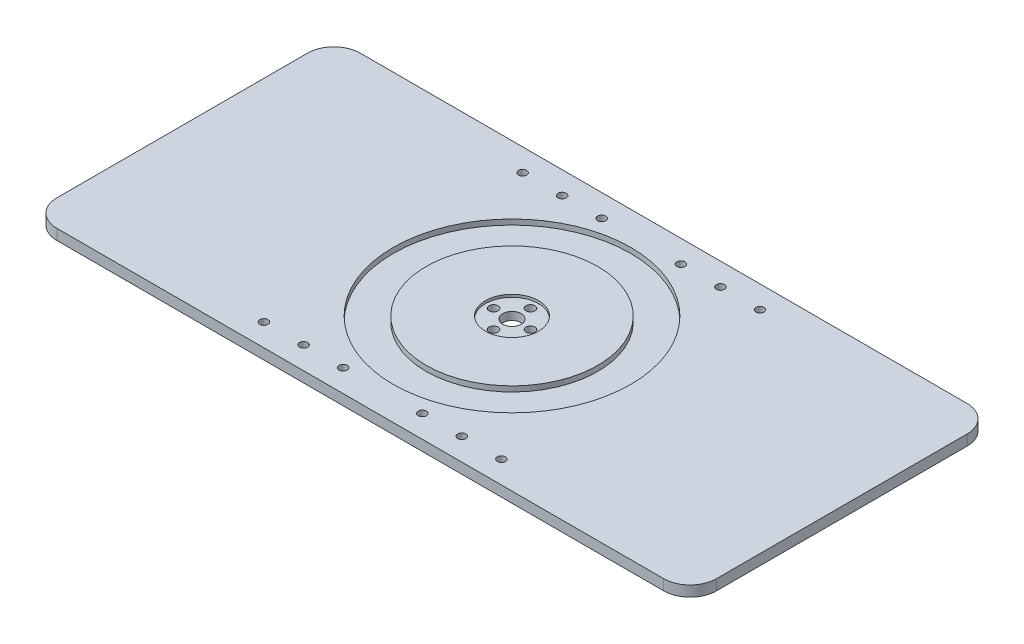
SolidWorks part; units mm, degrees
ref_plane "前视基准面" through (0, 0, 0) normal (0, 0, 1) x (1, 0, 0)
ref_plane "上视基准面" through (0, 0, 0) normal (0, 1, 0) x (1, 0, 0)
ref_plane "右视基准面" through (0, 0, 0) normal (1, 0, 0) x (0, 0, -1)
other "Configuration Table"
sketch "草图1" plane through (0, 0, 0) normal (0, 1, 0) x (1, 0, 0)
  line L0 (-93.4397, 0) -> (118.7468, 0) construction
  line L1 (-125, -57.5) -> (125, -57.5)
  line L2 (-125, -57.5) -> (-125, 57.5)
  line L3 (-125, 57.5) -> (125, 57.5)
  line L4 (125, -57.5) -> (125, 57.5)
  line L5 (-125, -57.5) -> (125, 57.5) construction
  line L6 (-125, 57.5) -> (125, -57.5) construction
  line L7 (0, 92.3971) -> (0, -129.74) construction
  circle A0 centre (0, 0) radius 45.1 construction
  circle A1 centre (0, 0) radius 3.5
  circle A2 centre (45, 49) radius 1.55
  circle A3 centre (45, -49) radius 1.55
  circle A4 centre (-45, -49) radius 1.55
  circle A5 centre (-45, 49) radius 1.55
  circle A6 centre (-15, -49) radius 1.55
  circle A7 centre (15, -49) radius 1.55
  circle A8 centre (15, 49) radius 1.55
  circle A9 centre (-15, 49) radius 1.55
  circle A10 centre (30, 49) radius 1.55
  circle A11 centre (-30, 49) radius 1.55
  circle A12 centre (-30, -49) radius 1.55
  circle A13 centre (30, -49) radius 1.55
  point P0 (0, 0)
  dimension "D3" = 90.2
  dimension "D4" = 7
  dimension "D7" = 3.1
  dimension "D9" = 3.1
  dimension "D1" = 250
  dimension "D2" = 115
  dimension "D5" = 98
  dimension "D6" = 90
  dimension "D8" = 30
extrude "凸台-拉伸1" add sketch "草图1" along normal blind 4
sketch "草图2" plane through (0, 4, 0) normal (0, 1, 0) x (1, 0, 0)
  circle A0 centre (0, 0) radius 45
  circle A1 centre (0, 0) radius 32.5
  dimension "D1" = 90
  dimension "D2" = 65
extrude "切除-拉伸1" cut sketch "草图2" against normal blind 2
sketch "草图3" plane through (0, 4, 0) normal (0, 1, 0) x (1, 0, 0)
  circle A0 centre (0, 0) radius 10.05
  circle A1 centre (0, 0) radius 7 construction
  circle A2 centre (0, 7) radius 1.7
  circle A4 centre (7, 0) radius 1.7
  circle A5 centre (0, -7) radius 1.7
  circle A6 centre (-7, 0) radius 1.7
  point P17 (0, 0)
  dimension "D1" = 20.1
  dimension "D2" = 14
  dimension "D3" = 3.4
  dimension "D4" = 4
extrude "切除-拉伸2" cut sketch "草图3" against normal blind 1
sketch "草图4" plane through (0, 3, 0) normal (0, 1, 0) x (1, 0, 0)
  circle A1 centre (7, 0) radius 1.7 construction
  circle A3 centre (7, 0) radius 1.7
  circle A4 centre (0, 7) radius 1.7 construction
  circle A5 centre (0, -7) radius 1.7 construction
  circle A6 centre (-7, 0) radius 1.7 construction
  circle A7 centre (0, 7) radius 1.7
  circle A8 centre (0, -7) radius 1.7
  circle A9 centre (-7, 0) radius 1.7
extrude "切除-拉伸5" cut sketch "草图4" against normal blind 20 and the other way blind 20
sketch "草图5" plane through (0, 4, 0) normal (0, 1, 0) x (1, 0, 0)
  line L0 (0, 0) -> (-29.8716, 29.8716) construction
  line L1 (0, 0) -> (0, 18.399) construction
  dimension "D1" = 45
fillet "圆角1" radius 10 4 edges at (125, 2, 57.5) (125, 2, -57.5) (-125, 2, -57.5) (-125, 2, 57.5)
